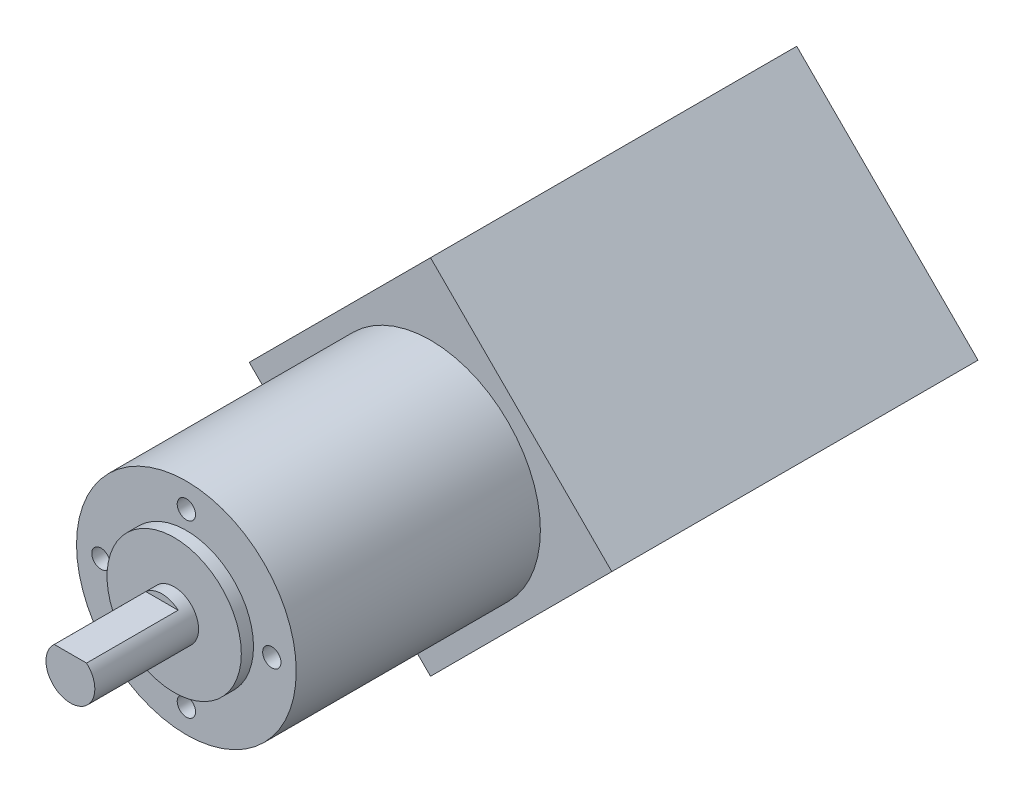
SolidWorks part; units mm, degrees
ref_plane "前视基准面" through (0, 0, 0) normal (0, 0, 1) x (1, 0, 0)
ref_plane "上视基准面" through (0, 0, 0) normal (0, 1, 0) x (1, 0, 0)
ref_plane "右视基准面" through (0, 0, 0) normal (1, 0, 0) x (0, 0, -1)
sketch "草图1" plane through (0, 0, 0) normal (0, 0, 1) x (1, 0, 0)
  line L1 (-29.6985, 0) -> (0, 29.6985)
  line L2 (-29.6985, 0) -> (0, -29.6985)
  line L3 (0, -29.6985) -> (29.6985, 0)
  line L4 (0, 29.6985) -> (29.6985, 0)
  line L5 (-29.6985, 0) -> (29.6985, 0) construction
  line L6 (0, -29.6985) -> (0, 29.6985) construction
  point P0 (0, 0)
  dimension "D1" = 42
extrude "凸台-拉伸1" add sketch "草图1" along normal blind 60
sketch "草图2" plane through (0, 0, 60) normal (0, 0, 1) x (1, 0, 0)
  circle A0 centre (0, 0) radius 18
  dimension "D1" = 36
extrude "凸台-拉伸2" add sketch "草图2" along normal blind 40
sketch "草图3" plane through (0, 0, 100) normal (0, 0, 1) x (1, 0, 0)
  circle A0 centre (0, 0) radius 11
  dimension "D1" = 22
extrude "凸台-拉伸3" add sketch "草图3" along normal blind 2
sketch "草图4" plane through (0, 0, 102) normal (0, 0, 1) x (1, 0, 0)
  circle A0 centre (0, 0) radius 4
  dimension "D1" = 8
extrude "凸台-拉伸4" add sketch "草图4" along normal blind 17
sketch "草图5" plane through (0, 0, 100) normal (0, 0, 1) x (1, 0, 0)
  circle A5 centre (0, 0) radius 14 construction
  circle A6 centre (0, 14) radius 1.5
  circle A7 centre (14, 0) radius 1.5
  circle A8 centre (0, -14) radius 1.5
  circle A9 centre (-14, 0) radius 1.5
  dimension "D1" = 28
extrude "切除-拉伸1" cut sketch "草图5" against normal blind 4
sketch "草图6" plane through (0, 0, 119) normal (0, 0, 1) x (1, 0, 0)
  line L0 (0, 4) -> (0, 3) construction
  line L1 (2.6458, 3) -> (-2.6458, 3)
  circle A0 centre (0, 0) radius 4 construction
  arc A1 (-2.6458, 3) -> (2.6458, 3) centre (0, 0) cw
extrude "切除-拉伸2" cut sketch "草图6" against normal blind 15
